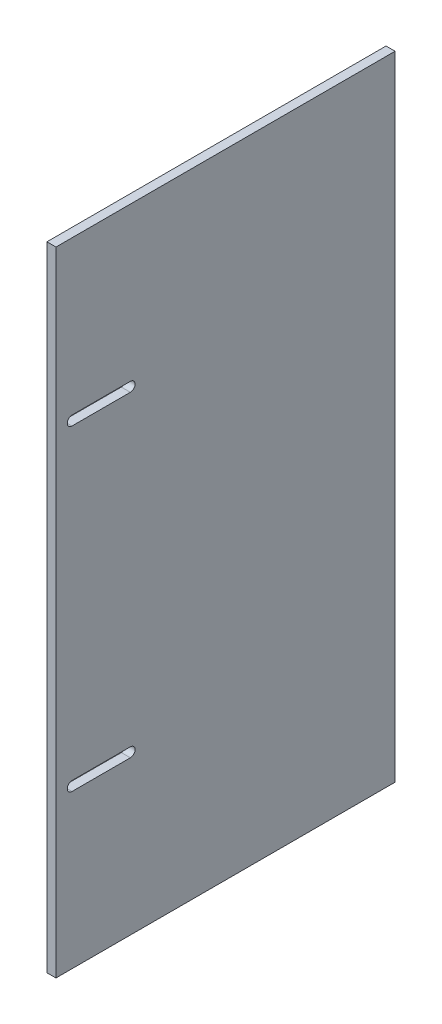
SolidWorks part; units mm, degrees
ref_plane "Front Plane" through (0, 0, 0) normal (1, 0, 0) x (0, 1, 0)
ref_plane "Top Plane" through (0, 0, 0) normal (0, 0, 1) x (0, 1, 0)
ref_plane "Right Plane" through (0, 0, 0) normal (0, 1, 0) x (-1, 0, 0)
sketch "Sketch1" plane through (0, 0, 0) normal (1, 0, 0) x (0, 1, 0)
  line L0 (0, 0) -> (280, 0)
  line L1 (280, 0) -> (280, 150)
  line L2 (280, 150) -> (0, 150)
  line L3 (0, 150) -> (0, 0)
  line L4 (70, 142.9) -> (70, 117.1) construction
  line L5 (67.9, 142.9) -> (67.9, 117.1)
  line L6 (72.1, 142.9) -> (72.1, 117.1)
  line L7 (140, 150) -> (140, 107.4822) construction
  line L8 (210, 142.9) -> (210, 117.1) construction
  line L9 (212.1, 142.9) -> (212.1, 117.1)
  line L10 (207.9, 142.9) -> (207.9, 117.1)
  arc A0 (67.9, 142.9) -> (72.1, 142.9) centre (70, 142.9) cw
  arc A1 (72.1, 117.1) -> (67.9, 117.1) centre (70, 117.1) cw
  arc A2 (212.1, 142.9) -> (207.9, 142.9) centre (210, 142.9) ccw
  arc A3 (207.9, 117.1) -> (212.1, 117.1) centre (210, 117.1) ccw
  point P7 (70, 130)
  point P14 (0, 0)
  point P17 (210, 130)
  point P22 (70, 112.0978)
  dimension "D1" = 150
  dimension "D2" = 280
  dimension "D3" = 4.2
  dimension "D4" = 5
  dimension "D5" = 140
  dimension "D6" = 30
extrude "Boss-Extrude1" add sketch "Sketch1" along normal blind 4
equation "\"D5@Sketch1\"=\"D2@Sketch1\"/2"
